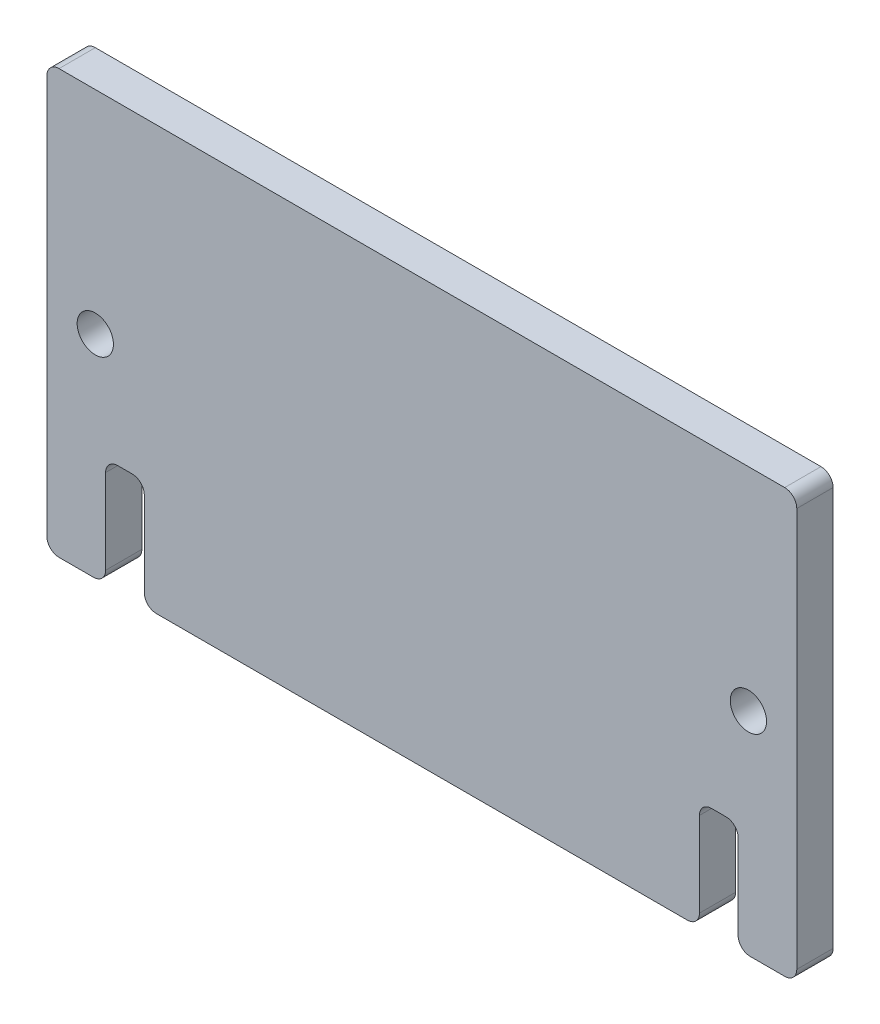
SolidWorks part; units mm, degrees
material "玻璃"
ref_plane "前视基准面" through (0, 0, 0) normal (0, 0, 1) x (1, 0, 0)
ref_plane "上视基准面" through (0, 0, 0) normal (0, 1, 0) x (1, 0, 0)
ref_plane "右视基准面" through (0, 0, 0) normal (1, 0, 0) x (0, 0, -1)
sketch "草图1" plane through (0, 0, 0) normal (0, 0, 1) x (1, 0, 0)
  line L0 (-27, 0) -> (27, 0) construction
  line L1 (-31, -17.5) -> (-26.15, -17.5)
  line L2 (-31, -17.5) -> (-31, 17.5)
  line L3 (-31, 17.5) -> (31, 17.5)
  line L4 (31, -17.5) -> (31, 17.5)
  line L5 (-31, -17.5) -> (31, 17.5) construction
  line L6 (-31, 17.5) -> (31, -17.5) construction
  line L7 (-26.15, -17.5) -> (-26.15, -8.5)
  line L8 (-26.15, -8.5) -> (-22.95, -8.5)
  line L9 (-22.95, -8.5) -> (-22.95, -17.5)
  line L10 (0, 0) -> (0, -17.5) construction
  line L11 (31, -17.5) -> (-31, 17.5) construction
  line L12 (22.95, -8.5) -> (22.95, -17.5)
  line L13 (26.15, -8.5) -> (22.95, -8.5)
  line L14 (26.15, -17.5) -> (26.15, -8.5)
  line L15 (-22.95, -17.5) -> (22.95, -17.5)
  line L16 (26.15, -17.5) -> (31, -17.5)
  circle A0 centre (-27, 0) radius 1.5
  circle A1 centre (27, 0) radius 1.5
  point P0 (0, 0)
  point P9 (0, 0)
  dimension "D3" = 3
  dimension "D1" = 35
  dimension "D2" = 62
  dimension "D4" = 54
  dimension "D5" = 45.9
  dimension "D6" = 3.2
  dimension "D7" = 9
extrude "凸台-拉伸1" add sketch "草图1" along normal blind 3
fillet "圆角1" radius 1 12 edges at (31, 17.5, 1.5) (-31, 17.5, 1.5) (-31, -17.5, 1.5) (31, -17.5, 1.5) (26.15, -8.5, 1.5) (22.95, -8.5, 1.5) (22.95, -17.5, 1.5) (26.15, -17.5, 1.5) (-22.95, -17.5, 1.5) (-22.95, -8.5, 1.5) (-26.15, -8.5, 1.5) (-26.15, -17.5, 1.5)
